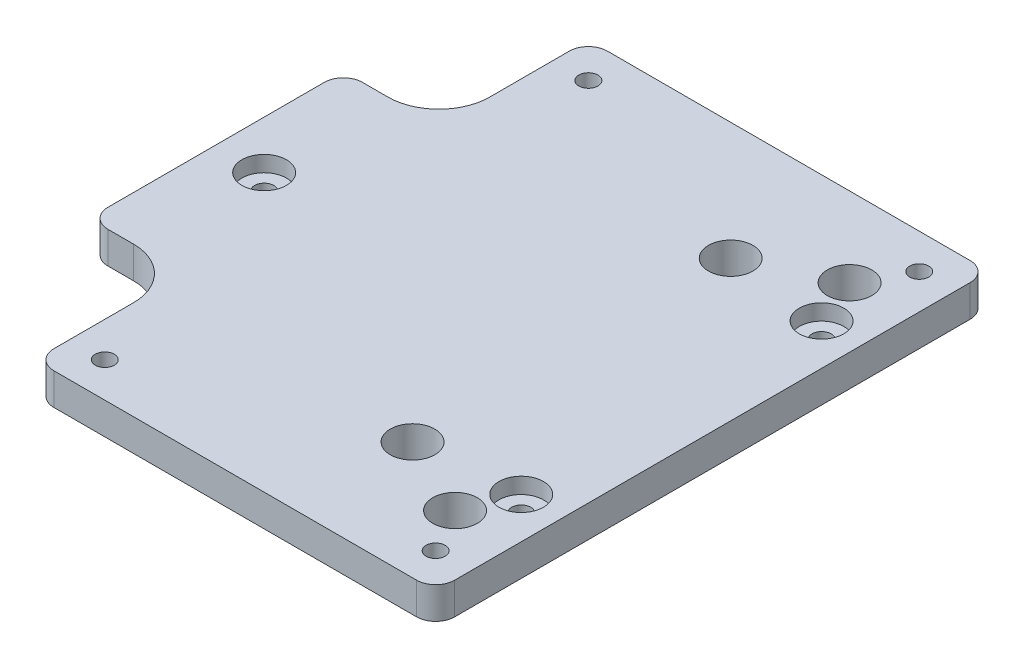
SolidWorks part; units mm, degrees
material "ABS"
ref_plane "Front Plane" through (0, 0, 0) normal (0, 0, 1) x (1, 0, 0)
ref_plane "Top Plane" through (0, 0, 0) normal (0, 1, 0) x (1, 0, 0)
ref_plane "Right Plane" through (0, 0, 0) normal (1, 0, 0) x (0, 0, -1)
sketch "Sketch1" plane through (0, 0, 0) normal (0, 1, 0) x (1, 0, 0)
  line L0 (-34, -43.5) -> (-34, 43.5)
  line L1 (-34, 43.5) -> (-97, 43.5)
  line L2 (-97, 43.5) -> (-97, 20)
  line L3 (-97, 20) -> (-112, 20)
  line L4 (-112, 20) -> (-112, -20)
  line L5 (-112, -20) -> (-97, -20)
  line L6 (-97, -20) -> (-97, -43.5)
  line L7 (-97, -43.5) -> (-34, -43.5)
  line L8 (-104.45, -14.5) -> (-104.45, 14.5) construction
  circle A0 centre (-56.13, -25) radius 2.85 construction
  circle A1 centre (-43.45, -31) radius 2.85 construction
  circle A2 centre (-56.13, 25) radius 2.85 construction
  circle A3 centre (-43.45, 31) radius 2.85 construction
  circle A5 centre (-104.45, 0) radius 1.5
  circle A8 centre (-40.45, 23.6) radius 1.5 construction
  circle A9 centre (-40.45, -23.6) radius 1.5 construction
  circle A10 centre (-56.13, -25) radius 2.85 construction
  circle A11 centre (-43.45, -31) radius 2.85 construction
  circle A12 centre (-56.13, 25) radius 2.85 construction
  circle A13 centre (-43.45, 31) radius 2.85 construction
  circle A14 centre (-104.45, 14.5) radius 1.25 construction
  circle A15 centre (-104.45, -14.5) radius 1.25 construction
  circle A16 centre (-43.45, 31) radius 3.5
  circle A17 centre (-56.13, 25) radius 3.5
  circle A18 centre (-40.45, 23.6) radius 1.5
  circle A19 centre (-40.45, -23.6) radius 1.5
  circle A20 centre (-56.13, -25) radius 3.5
  circle A21 centre (-43.45, -31) radius 3.5
  circle A22 centre (-39.5, 38) radius 1.5
  circle A23 centre (-91.5, 38) radius 1.5
  circle A24 centre (-91.5, -38) radius 1.5
  circle A25 centre (-39.5, -38) radius 1.5
  point P38 (-34, 0)
  point P39 (-112, 0)
  point P40 (0, 0)
  point P49 (0, 0)
  point P50 (-104.45, 0)
  dimension "D6" = 2.5
  dimension "D7" = 2.5
  dimension "D10" = 7
  dimension "D13" = 3
  dimension "D16" = 3
  dimension "D1" = 87
  dimension "D2" = 63
  dimension "D3" = 40
  dimension "D4" = 15
  dimension "D5" = 34
  dimension "D8" = 29
  dimension "D9" = 29
  dimension "62" = 64
  dimension "D11" = 52
  dimension "D12" = 76
  dimension "D14" = 5.5
  dimension "D15" = 5.5
extrude "Boss-Extrude1" add sketch "Sketch1" along normal blind 5
fillet "Fillet1" radius 3 6 edges at (-112, 2.5, 20) (-112, 2.5, -20) (-97, 2.5, -43.5) (-34, 2.5, -43.5) (-34, 2.5, 43.5) (-97, 2.5, 43.5)
fillet "Fillet2" radius 8 2 edges at (-97, 2.5, -20) (-97, 2.5, 20)
sketch "Sketch2" plane through (0, 5, 0) normal (0, 1, 0) x (1, 0, 0)
  circle A0 centre (-40.45, 23.6) radius 1.5 construction
  circle A1 centre (-40.45, -23.6) radius 1.5 construction
  circle A4 centre (-40.45, 23.6) radius 1.5 construction
  circle A5 centre (-40.45, -23.6) radius 1.5 construction
  circle A8 centre (-40.45, -23.6) radius 3.5
  circle A9 centre (-40.45, 23.6) radius 3.5
  circle A12 centre (-104.45, 0) radius 1.5 construction
  circle A13 centre (-104.45, 0) radius 1.5 construction
  circle A14 centre (-104.45, 0) radius 3.5
  dimension "D1" = 7
  dimension "D2" = 7
extrude "Cut-Extrude1" cut sketch "Sketch2" against normal blind 2.5
sketch "Sketch3" plane through (0, 0, 0) normal (0, -1, 0) x (1, 0, 0)
  line L1 (-37.8979, 35.225) -> (-36.2957, 38)
  line L2 (-36.2957, 38) -> (-37.8979, 40.775)
  line L3 (-37.8979, 40.775) -> (-41.1021, 40.775)
  line L4 (-41.1021, 40.775) -> (-42.7043, 38)
  line L5 (-42.7043, 38) -> (-41.1021, 35.225)
  line L6 (-41.1021, 35.225) -> (-37.8979, 35.225)
  line L25 (-89.8979, 35.225) -> (-88.2957, 38)
  line L26 (-88.2957, 38) -> (-89.8979, 40.775)
  line L27 (-89.8979, 40.775) -> (-93.1021, 40.775)
  line L28 (-93.1021, 40.775) -> (-94.7043, 38)
  line L29 (-94.7043, 38) -> (-93.1021, 35.225)
  line L30 (-93.1021, 35.225) -> (-89.8979, 35.225)
  line L31 (-89.9123, -35.25) -> (-93.0877, -35.25)
  line L32 (-93.0877, -35.25) -> (-94.6754, -38)
  line L33 (-94.6754, -38) -> (-93.0877, -40.75)
  line L34 (-93.0877, -40.75) -> (-89.9123, -40.75)
  line L35 (-89.9123, -40.75) -> (-88.3246, -38)
  line L36 (-88.3246, -38) -> (-89.9123, -35.25)
  line L37 (-37.9123, -40.75) -> (-36.3246, -38)
  line L38 (-36.3246, -38) -> (-37.9123, -35.25)
  line L39 (-37.9123, -35.25) -> (-41.0877, -35.25)
  line L40 (-41.0877, -35.25) -> (-42.6754, -38)
  line L41 (-42.6754, -38) -> (-41.0877, -40.75)
  line L42 (-41.0877, -40.75) -> (-37.9123, -40.75)
  circle A0 centre (-39.5, 38) radius 2.775 construction
  circle A2 centre (-91.5, 38) radius 2.775 construction
  circle A3 centre (-91.5, -38) radius 2.75 construction
  circle A4 centre (-39.5, -38) radius 2.75 construction
  point P26 (-89.0968, 36.6125)
  dimension "D1" = 5.55
  dimension "D2" = 5.55
  dimension "D3" = 5.5
  dimension "D4" = 5.5
extrude "Cut-Extrude2" cut sketch "Sketch3" against normal blind 2
